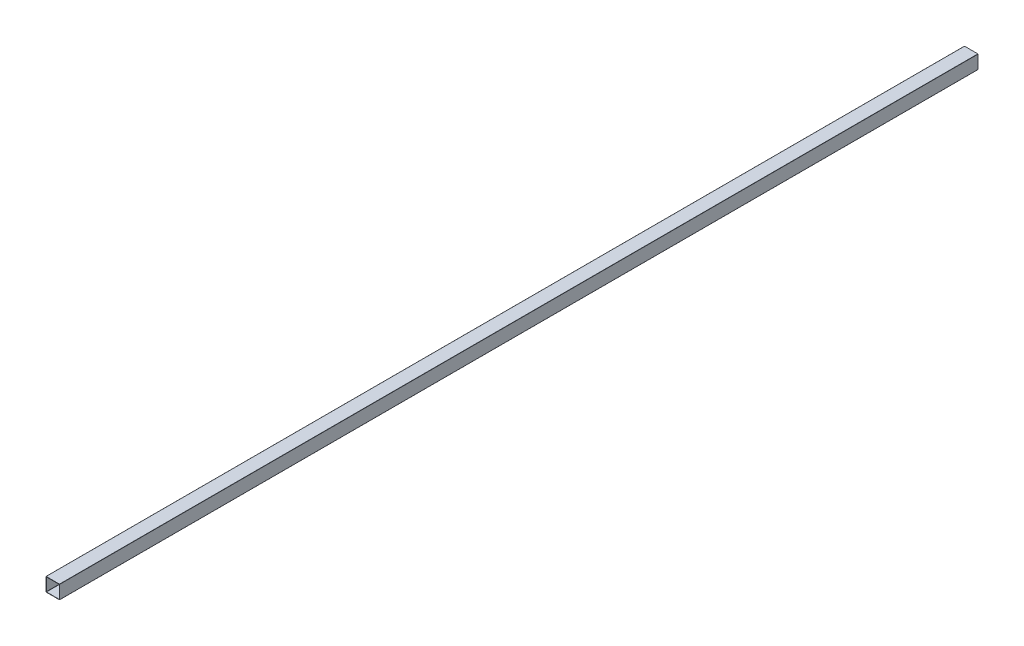
SolidWorks part; units mm, degrees
material "AISI 1035 Acero (SS)"
ref_plane "Alzado" through (0, 0, 0) normal (0, 0, 1) x (1, 0, 0)
ref_plane "Planta" through (0, 0, 0) normal (0, 1, 0) x (1, 0, 0)
ref_plane "Vista lateral" through (0, 0, 0) normal (1, 0, 0) x (0, 0, -1)
sketch "Croquis1" plane through (0, 0, 0) normal (0, 0, 1) x (1, 0, 0)
  line L0 (-42.56, -42.56) -> (-42.56, 42.56)
  line L1 (-44.45, -44.45) -> (44.45, -44.45)
  line L2 (-44.45, -44.45) -> (-44.45, 44.45)
  line L3 (-44.45, 44.45) -> (44.45, 44.45)
  line L4 (44.45, -44.45) -> (44.45, 44.45)
  line L5 (-44.45, -44.45) -> (44.45, 44.45) construction
  line L6 (-44.45, 44.45) -> (44.45, -44.45) construction
  line L7 (-42.56, 42.56) -> (42.56, 42.56)
  line L8 (42.56, -42.56) -> (42.56, 42.56)
  line L9 (-42.56, -42.56) -> (42.56, -42.56)
  point P0 (0, 0)
  dimension "D1" = 88.9
  dimension "D3" = 1.89
extrude "Saliente-Extruir1" add sketch "Croquis1" against normal blind 6000
fillet "Redondeo1" radius 1 8 edges at (-42.56, 42.56, -3000) (42.56, 42.56, -3000) (42.56, -42.56, -3000) (-44.45, -44.45, -3000) (-44.45, 44.45, -3000) (-42.56, -42.56, -3000) (44.45, -44.45, -3000) (44.45, 44.45, -3000)
